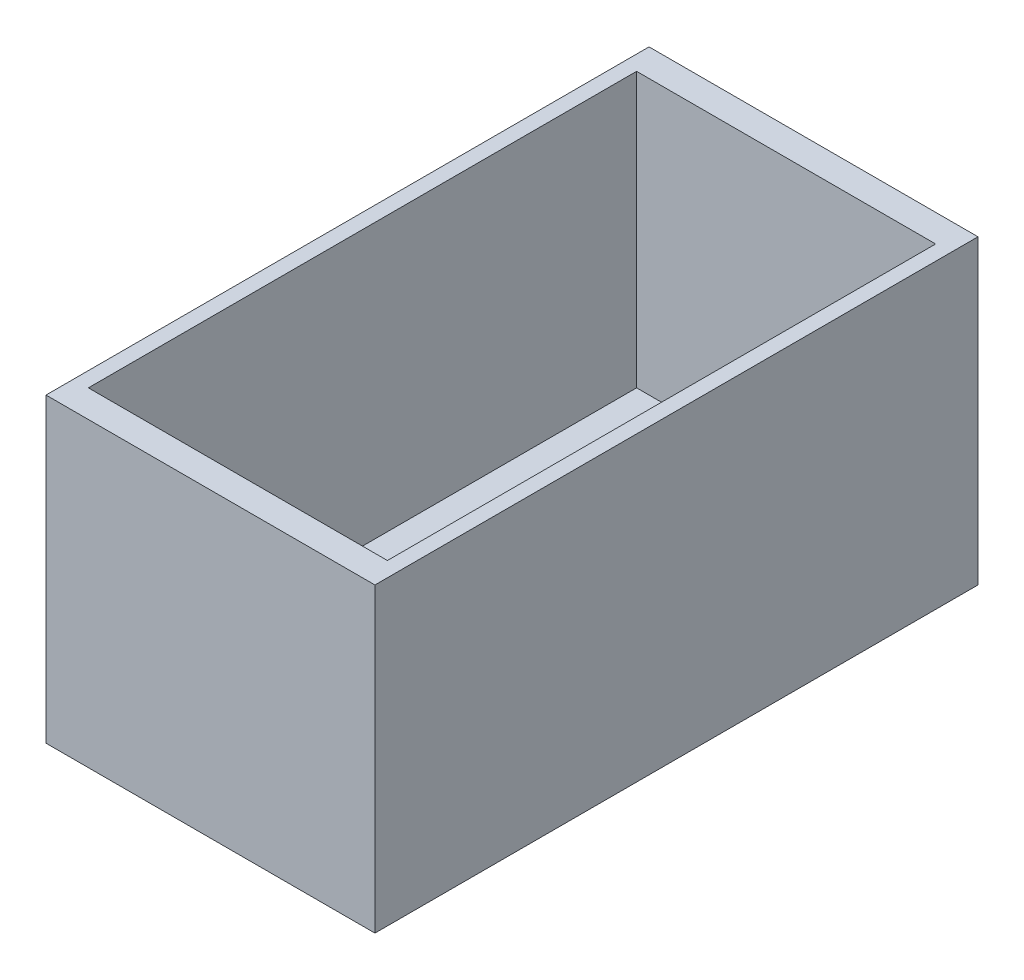
SolidWorks part; units mm, degrees
ref_plane "Plano frontal" through (0, 0, 0) normal (0, 0, 1) x (1, 0, 0)
ref_plane "Plano superior" through (0, 0, 0) normal (0, 1, 0) x (1, 0, 0)
ref_plane "Plano direito" through (0, 0, 0) normal (1, 0, 0) x (0, 0, -1)
sketch "Esboço1" plane through (0, 0, 0) normal (0, 1, 0) x (1, 0, 0)
  line L1 (-30, 55) -> (30, 55)
  line L2 (-30, 55) -> (-30, -55)
  line L3 (-30, -55) -> (30, -55)
  line L4 (30, 55) -> (30, -55)
  line L5 (-30, 55) -> (30, -55) construction
  line L6 (-30, -55) -> (30, 55) construction
  point P0 (0, 0)
  dimension "D1" = 110
  dimension "D2" = 60
extrude "Ressalto-extrusão1" add sketch "Esboço1" along normal blind 5
sketch "Esboço2" plane through (0, 5, 0) normal (0, 1, 0) x (1, 0, 0)
  line L0 (30, -55) -> (30, 55) construction
  line L1 (-30, 55) -> (30, 55)
  line L2 (-30, 55) -> (-30, -55)
  line L3 (-30, -55) -> (30, -55)
  line L4 (30, 55) -> (30, -55)
  line L5 (-30, 55) -> (30, -55) construction
  line L6 (-30, -55) -> (30, 55) construction
  line L8 (-27.2727, 50) -> (27.2727, 50)
  line L9 (-27.2727, 50) -> (-27.2727, -50)
  line L10 (-27.2727, -50) -> (27.2727, -50)
  line L11 (27.2727, 50) -> (27.2727, -50)
  line L12 (-27.2727, 50) -> (27.2727, -50) construction
  line L13 (-27.2727, -50) -> (27.2727, 50) construction
  point P0 (0, 0)
  point P8 (0, 0)
  dimension "D1" = 110
  dimension "D2" = 100
extrude "Ressalto-extrusão2" add sketch "Esboço2" along normal blind 50
